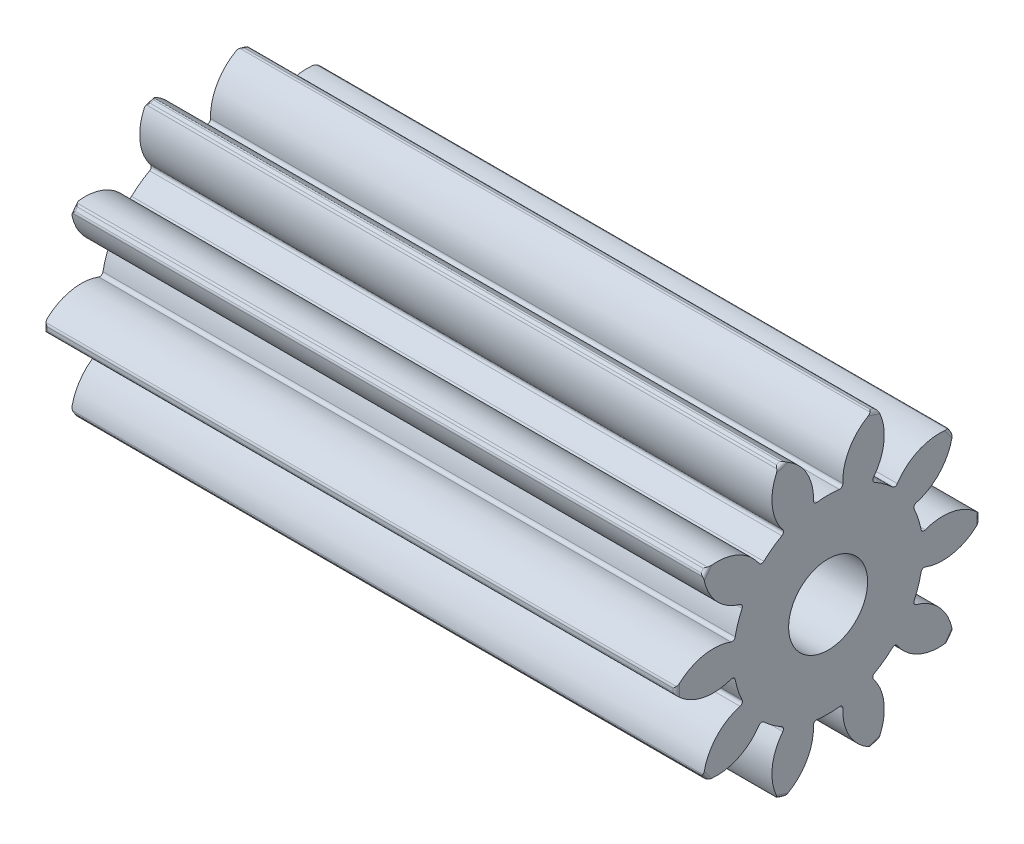
SolidWorks part; units mm, degrees
ref_plane "Plane1" through (0, 0, 0) normal (0, 0, 1) x (1, 0, 0)
ref_plane "Plane2" through (0, 0, 0) normal (0, 1, 0) x (1, 0, 0)
ref_plane "Plane3" through (0, 0, 0) normal (1, 0, 0) x (0, 0, -1)
other "Configuration Table"
sketch "HoldingSke" plane through (0, 0, 0) normal (0, 1, 0) x (1, 0, 0)
  line L0 (0, 0) -> (2.462, -0.4341)
  line L1 (-15, 0) -> (100, 0) construction
  line L2 (0, 0) -> (-2.1039, 2.3779)
  line L3 (0, 0) -> (-11.863, 4.5341)
  line L4 (0, 0) -> (8.5048, 1.4996)
  line L5 (0, 0) -> (-46.8476, -17.4728)
  line L6 (0, 0) -> (-9.9476, -6.7116)
  line L7 (-2.1039, 2.3779) -> (8.6586, 51.2059)
  line L8 (-76.2, 54.61) -> (-76.1, 54.61)
  line L9 (-71.009, 38.7566) -> (-53.1078, 45.2721)
  line L10 (-76.2, 71.12) -> (104.1128, 71.12)
  line L11 (0, 0) -> (-12, 0)
  line L12 (-76.2, 101.6) -> (-76.185, 101.6)
  line L13 (24.9733, 27.94) -> (52.9518, 28.4284)
  line L14 (24.9733, 27.94) -> (24.9743, 27.94)
  line L15 (24.9733, 27.94) -> (100.4006, 29.5858)
  line L16 (-63.627, -0.4) -> (-12.827, -0.4)
  circle A0 centre (0, 0) radius 0.625
  circle A1 centre (0, 0) radius 1.499
  circle A2 centre (0, 0) radius 37.5
  circle A3 centre (0, 0) radius 0.625
  dimension "MHD" = 2.998
  dimension "Hub_dia" = 75
  dimension "Bore" = 1.25
  dimension "MBD" = 1.25
  dimension "Num_teeth" = 10
  dimension "Pitch" = 2.5
  dimension "Overall_len" = 50
  dimension "Show_teeth" = 10
  dimension "Thickness" = 12
  dimension "OAL" = 50.0001
  dimension "T_dim" = 0.1
  dimension "Ap" = 20
  dimension "H" = 19.05
  dimension "Pitch_radius" = 180.3128
  dimension "Width" = 12
  dimension "Backlash" = 0.015
  dimension "Addendum_fac" = 1
  dimension "Dedendum_fac" = 1.25
  dimension "Clearance_fac" = 0.25
  dimension "Dedendum_add" = 0.001
  dimension "Module" = 0.4
sketch "BasProSke" plane through (0, 0, 0) normal (0, 1, 0) x (1, 0, 0)
  line L0 (-10, 0) -> (60, 0) construction
  line L1 (0, 0) -> (0, 2.4)
  line L2 (0, 0) -> (12, 0)
  line L3 (12, 0) -> (12, 2.4)
  line L4 (12, 2.4) -> (0, 2.4)
  dimension "Thickness" = 12
  dimension "Diameter" = 4.8
revolve "Base-Revolve" add sketch "BasProSke" angle 360 about L0
sketch "TooCutSke" plane through (0, 0, 0) normal (1, 0, 0) x (0, 0, -1)
  line L1 (0, 0) -> (0, 107) construction
  line L2 (0, 0) -> (-0.3391, 1.971) construction
  line L3 (0, 0) -> (-1.2233, 3.765) construction
  line L4 (-0.3391, 1.971) -> (-0.6117, 1.8825) construction
  arc A0 (0.2369, 1.4802) -> (-0.2369, 1.4802) centre (0, 0) ccw
  arc A1 (0.7316, 2.3124) -> (-0.7316, 2.3124) centre (0, 0) ccw
  circle A2 centre (0, 0) radius 2 construction
  circle A3 centre (0, 0) radius 1.8794 construction
  arc A4 (-0.2369, 1.4802) -> (-0.7316, 2.3124) centre (-1.0318, 1.5708) ccw
  arc A5 (0.7316, 2.3124) -> (0.2369, 1.4802) centre (1.0318, 1.5708) ccw
  dimension "Root_dia" = 2.998
  dimension "Overcut_dia" = 4.8508
  dimension "Pitch_dia" = 4
  dimension "Base_dia" = 3.7588
  dimension "Flank_rad" = 0.8
  dimension "Half_ang" = 18
  dimension "Half_CT" = 0.2866
extrude "ToothCut" cut sketch "TooCutSke" along normal through all
fillet "Breaks" [suppressed] radius 0.008
fillet "RootFillets" [suppressed] radius 0.101
pattern_circular "TeethCuts" count 10 every 36 about axis through (-10, 0, 0) along (1, 0, 0) of "ToothCut", "RootFillets", "Breaks"
sketch "HubNeaOneSke" plane through (0, 0, 0) normal (-1, 0, 0) x (0, 0, 1)
  circle A0 centre (0, 0) radius 1.499
  dimension "Diameter" = 2.998
extrude "HubNearOne" [suppressed] add sketch "HubNeaOneSke" along normal blind 38.0001
sketch "HubNeaBotSke" plane through (0, 0, 0) normal (-1, 0, 0) x (0, 0, 1)
  circle A0 centre (0, 0) radius 1.499
  dimension "Diameter" = 2.998
extrude "HubNearBoth" [suppressed] add sketch "HubNeaBotSke" along normal blind 19
ref_plane "FarPln" through (12, 0, 0) normal (1, 0, 0) x (0, 0, -1)
sketch "HubFarSke" plane through (12, 0, 0) normal (1, 0, 0) x (0, 0, -1)
  circle A0 centre (0, 0) radius 1.499
  dimension "Diameter" = 2.998
extrude "HubFar" [suppressed] add sketch "HubFarSke" along normal blind 19
sketch "BorSke" plane through (0, 0, 0) normal (1, 0, 0) x (0, 0, -1)
  circle A0 centre (0, 0) radius 0.625
  dimension "Diameter" = 1.25
extrude "Bore" cut sketch "BorSke" along normal mid plane 100.0001
sketch "KeySke" plane through (0, 0, 0) normal (1, 0, 0) x (0, 0, -1)
  line L0 (-0.05, 0) -> (-0.05, 0.725)
  line L1 (-0.05, 0.725) -> (0.05, 0.725)
  line L2 (0.05, 0.725) -> (0.05, 0)
  line L3 (0, 0) -> (0, 34) construction
  line L4 (-0.05, 0) -> (0.05, 0)
  dimension "Offset" = 0.725
  dimension "Width" = 0.1
extrude "Keyway" [suppressed] cut sketch "KeySke" along normal mid plane 100.0001
pattern_circular "Keyway2" [suppressed] count 2 every 90 about axis through (-10, 0, 0) along (1, 0, 0)
sketch "Sketch1" plane through (12, 0, 0) normal (1, 0, 0) x (0, 0, -1)
  line L1 (-12.2038, -11.0729) -> (4.5032, -11.0729)
  line L2 (-12.2038, -11.0729) -> (-12.2038, 4.2267)
  line L3 (-12.2038, 4.2267) -> (4.5032, 4.2267)
  line L4 (4.5032, -11.0729) -> (4.5032, 4.2267)
  line L5 (-12.2038, -11.0729) -> (4.5032, 4.2267) construction
  line L6 (-12.2038, 4.2267) -> (4.5032, -11.0729) construction
  point P0 (-3.8503, -3.4231)
extrude "Cut-Extrude1" cut sketch "Sketch1" against normal blind 2
fillet "Fillet1" radius 0.05 2 edges at (5, -0.6827, -1.3345) (5, -0.2321, -1.4809)
fillet "Fillet2" radius 0.05 18 edges at (5, 0.6827, -1.3345) (5, 0.2321, -1.4809) (5, 1.3367, -0.6783) (5, 1.0582, -1.0617) (5, 1.4802, 0.2369) (5, 1.4802, -0.2369) (5, 1.0582, 1.0617) (5, 1.3367, 0.6783) (5, 0.2321, 1.4809) (5, 0.6827, 1.3345) (5, -0.6827, 1.3345) (5, -0.2321, 1.4809) (5, -1.3367, 0.6783) (5, -1.0582, 1.0617) (5, -1.4802, -0.2369) (5, -1.4802, 0.2369) (5, -1.3367, -0.6783) (5, -1.0582, -1.0617)
fillet "Fillet3" radius 0.05 40 edges at (0, 0, -2.4) (5, -0.048, -2.3995) (10, 0, -2.4) (5, 0.048, -2.3995) (0, 1.4107, -1.9416) (5, 1.3716, -1.9695) (10, 1.4107, -1.9416) (5, 1.4492, -1.9131) (0, 2.2825, -0.7416) (5, 2.2673, -0.7871) (10, 2.2825, -0.7416) (5, 2.2969, -0.6959) (0, 2.2825, 0.7416) (5, 2.2969, 0.6959) (10, 2.2825, 0.7416) (5, 2.2673, 0.7871) (0, 1.4107, 1.9416) (5, 1.4492, 1.9131) (10, 1.4107, 1.9416) (5, 1.3716, 1.9695) (0, 0, 2.4) (5, 0.048, 2.3995) (10, 0, 2.4) (5, -0.048, 2.3995) (0, -1.4107, 1.9416) (5, -1.3716, 1.9695) (10, -1.4107, 1.9416) (5, -1.4492, 1.9131) (0, -2.2825, 0.7416) (5, -2.2673, 0.7871) (10, -2.2825, 0.7416) (5, -2.2969, 0.6959) (0, -2.2825, -0.7416) (5, -2.2969, -0.6959) (10, -2.2825, -0.7416) (5, -2.2673, -0.7871) (0, -1.4107, -1.9416) (5, -1.4492, -1.9131) (10, -1.4107, -1.9416) (5, -1.3716, -1.9695)
equation "' \"Module@HoldingSke\" = 6.35"
equation "' \"Num_teeth@HoldingSke\" = 12"
equation "' \"Ap@HoldingSke\" =  20"
equation "' \"Ap@HoldingSke\" = 20"
equation "' \"Width@HoldingSke\" = 0.5 * 25.4"
equation "' \"Hub_dia@HoldingSke\"= 1 * 25.4"
equation "' \"Hub_dia@HoldingSke\" = 1 * 25.4"
equation "' \"Overall_len@HoldingSke\" = 1.0 * 25.4"
equation "' \"Bore@HoldingSke\" = 0.75 * 25.4"
equation "' \"T_dim@HoldingSke\" = 0.1 * 25.4"
equation "' \"Width@KeySke\" = 0.25 * 25.4"
equation "' \"Show_teeth@HoldingSke\" = 13"
equation "' \"Backlash@HoldingSke\" = 0.009 * 25.4"
equation "' \"Addendum_fac@HoldingSke\" = 1.0"
equation "' \"Dedendum_fac@HoldingSke\" = 1.25"
equation "' \"Dedendum_add@HoldingSke\" = 0.00005 * 25.4"
equation "' \"Clearance_fac@HoldingSke\" = 0.25"
equation "\"Pitch@HoldingSke\" = 1 / \"Module@HoldingSke\""
equation "\"Overcut_dia@TooCutSke\" = (\"Num_teeth@HoldingSke\" + 2 * \"Addendum_fac@HoldingSke\") / \"Pitch@HoldingSke\" + 0.002 * 25.4"
equation "\"Pitch_dia@TooCutSke\" = \"Num_teeth@HoldingSke\" / \"Pitch@HoldingSke\""
equation "\"Base_dia@TooCutSke\" = \"Num_teeth@HoldingSke\" / \"Pitch@HoldingSke\" * cos((\"Ap@HoldingSke\"  * 3.14159265 / 180))"
equation "\"Root_dia@TooCutSke\" = (\"Num_teeth@HoldingSke\" + 2) / \"Pitch@HoldingSke\" - 2 * (\"Addendum_fac@HoldingSke\" + \"Dedendum_fac@HoldingSke\") / \"Pitch@HoldingSke\" - \"Dedendum_add@HoldingSke\" * 2"
equation "\"Half_ang@TooCutSke\" = 180 / \"Num_teeth@HoldingSke\""
equation "\"Half_CT@TooCutSke\" = \"Num_teeth@HoldingSke\" / \"Pitch@HoldingSke\" * sin((3.14159265 / 2 / \"Num_teeth@HoldingSke\")) / 2 - 7 * \"Backlash@HoldingSke\" / 4"
equation "\"Flank_rad@TooCutSke\" = \"Num_teeth@HoldingSke\" / \"Pitch@HoldingSke\" / 5"
equation "\"Radius@RootFillets\" = \"Clearance_fac@HoldingSke\" / \"Pitch@HoldingSke\" + \"Dedendum_add@HoldingSke\""
equation "\"Break_rad@Breaks\" = 0.02 / \"Pitch@HoldingSke\""
equation "\"Thickness@HoldingSke\" = \"Width@HoldingSke\""
equation "\"OAL@HoldingSke\" = \"Thickness@HoldingSke\""
equation "\"MHD@HoldingSke\" = (\"Num_teeth@HoldingSke\" + 2) / \"Pitch@HoldingSke\" - 2 * (\"Addendum_fac@HoldingSke\" + \"Dedendum_fac@HoldingSke\")  / \"Pitch@HoldingSke\" - \"Dedendum_add@HoldingSke\" * 2"
equation "\"MBD@HoldingSke\" = (\"Num_teeth@HoldingSke\" + 2) / \"Pitch@HoldingSke\" - 2 * (\"Addendum_fac@HoldingSke\" + \"Dedendum_fac@HoldingSke\")  / \"Pitch@HoldingSke\" - \"Dedendum_add@HoldingSke\" * 2 - 0.002 * 25.4"
equation "\"MHD@HoldingSke\" = ((sgn( \"MHD@HoldingSke\" - \"Hub_dia@HoldingSke\" )-1)*( \"MHD@HoldingSke\" - \"Hub_dia@HoldingSke\" ))/-2+ \"Hub_dia@HoldingSke\""
equation "\"MBD@HoldingSke\" = ((sgn( \"MBD@HoldingSke\" - \"Bore@HoldingSke\" )-1)*( \"MBD@HoldingSke\" - \"Bore@HoldingSke\" ))/-2+ \"Bore@HoldingSke\""
equation "\"OAL@HoldingSke\" = ((sgn( \"OAL@HoldingSke\" - \"Overall_len@HoldingSke\" )+1)*( \"OAL@HoldingSke\" - \"Overall_len@HoldingSke\" ))/2 + \"Overall_len@HoldingSke\" + 0.000002 * 25.4"
equation "\"Num_teeth@TeethCuts\" = int( \"Show_teeth@HoldingSke\" ) + 1"
equation "\"Num_teeth@TeethCuts\" = ((sgn( \"Num_teeth@TeethCuts\" - \"Num_teeth@HoldingSke\" )-1)*( \"Num_teeth@TeethCuts\" - \"Num_teeth@HoldingSke\" ))/-2+ \"Num_teeth@HoldingSke\""
equation "\"Num_teeth@TeethCuts\" = ((sgn( \"Num_teeth@TeethCuts\" - 2.0)+1)*( \"Num_teeth@TeethCuts\" - 2.0))/2 +2.0"
equation "\"Angle@TeethCuts\" = 360.0 / \"Num_teeth@HoldingSke\""
equation "\"Diameter@BasProSke\" = (\"Num_teeth@HoldingSke\" + 2 * \"Addendum_fac@HoldingSke\") / \"Pitch@HoldingSke\""
equation "\"Thickness@BasProSke\"  = \"Thickness@HoldingSke\""
equation "' \"Fillet_rad@BasProSke\" =  \"Thickness@HoldingSke\" * 0.05"
equation "' \"Fillet_rad@BasProSke\" = \"Thickness@HoldingSke\" * 0.05"
equation "\"MHD@HoldingSke\" = ((sgn( \"MHD@HoldingSke\" - \"Root_dia@TooCutSke\" )-1)*( \"MHD@HoldingSke\" - \"Root_dia@TooCutSke\" ))/-2+ \"Root_dia@TooCutSke\""
equation "\"Diameter@HubNeaOneSke\" = \"MHD@HoldingSke\""
equation "\"Length@HubNearOne\" = \"OAL@HoldingSke\" - \"Thickness@BasProSke\""
equation "\"Diameter@HubNeaBotSke\" = \"MHD@HoldingSke\""
equation "\"Length@HubNearBoth\" = ( \"OAL@HoldingSke\" - \"Thickness@BasProSke\" ) / 2.0"
equation "\"Thickness@FarPln\" = \"Thickness@BasProSke\""
equation "\"Diameter@HubFarSke\" = \"MHD@HoldingSke\""
equation "\"Length@HubFar\" = ( \"OAL@HoldingSke\" - \"Thickness@BasProSke\" ) / 2.0"
equation "\"Diameter@BorSke\" = \"MBD@HoldingSke\""
equation "\"D1@Bore\" = \"OAL@HoldingSke\" * 2.0"
equation "\"D1@Keyway\" = \"OAL@HoldingSke\" * 2.0"
equation "\"Offset@KeySke\" = \"T_dim@HoldingSke\" + \"MBD@HoldingSke\" / 2.0"
